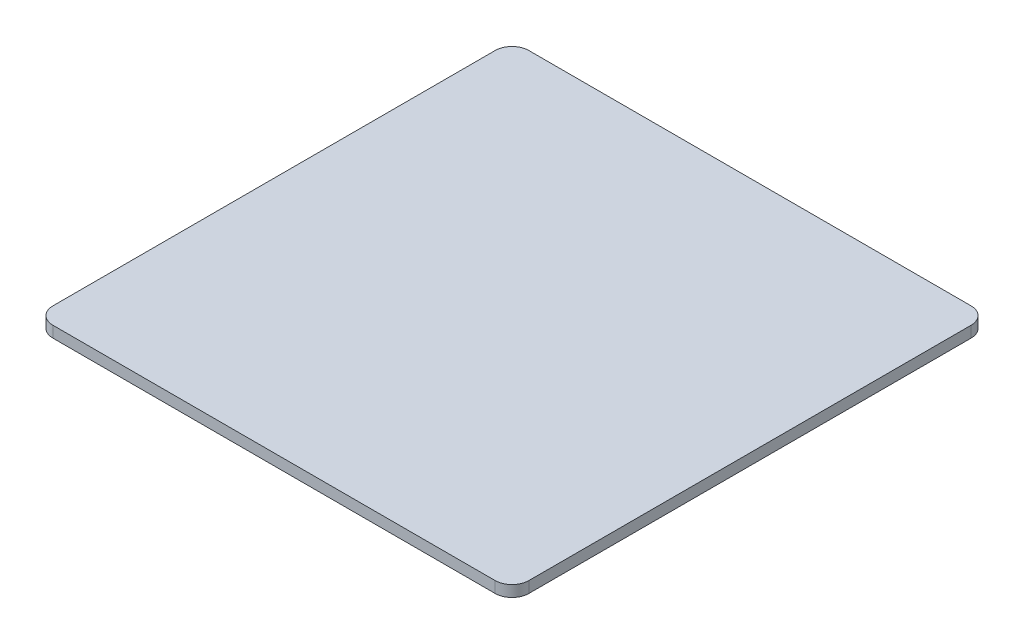
SolidWorks part; units mm, degrees
ref_plane "Front Plane" through (0, 0, 0) normal (0, 0, 1) x (1, 0, 0)
ref_plane "Top Plane" through (0, 0, 0) normal (0, 1, 0) x (1, 0, 0)
ref_plane "Right Plane" through (0, 0, 0) normal (1, 0, 0) x (0, 0, -1)
sketch "Sketch1" plane through (0, 0, 0) normal (0, 1, 0) x (1, 0, 0)
  line L1 (-42.5, -42.5) -> (42.5, -42.5)
  line L2 (-42.5, -42.5) -> (-42.5, 42.5)
  line L3 (-42.5, 42.5) -> (42.5, 42.5)
  line L4 (42.5, -42.5) -> (42.5, 42.5)
  line L5 (-42.5, -42.5) -> (42.5, 42.5) construction
  line L6 (-42.5, 42.5) -> (42.5, -42.5) construction
  point P0 (0, 0)
  dimension "D1" = 85
  dimension "D2" = 85
extrude "Boss-Extrude1" add sketch "Sketch1" along normal blind 2
fillet "Fillet1" radius 3 4 edges at (-42.5, 1, -42.5) (42.5, 1, -42.5) (42.5, 1, 42.5) (-42.5, 1, 42.5)
